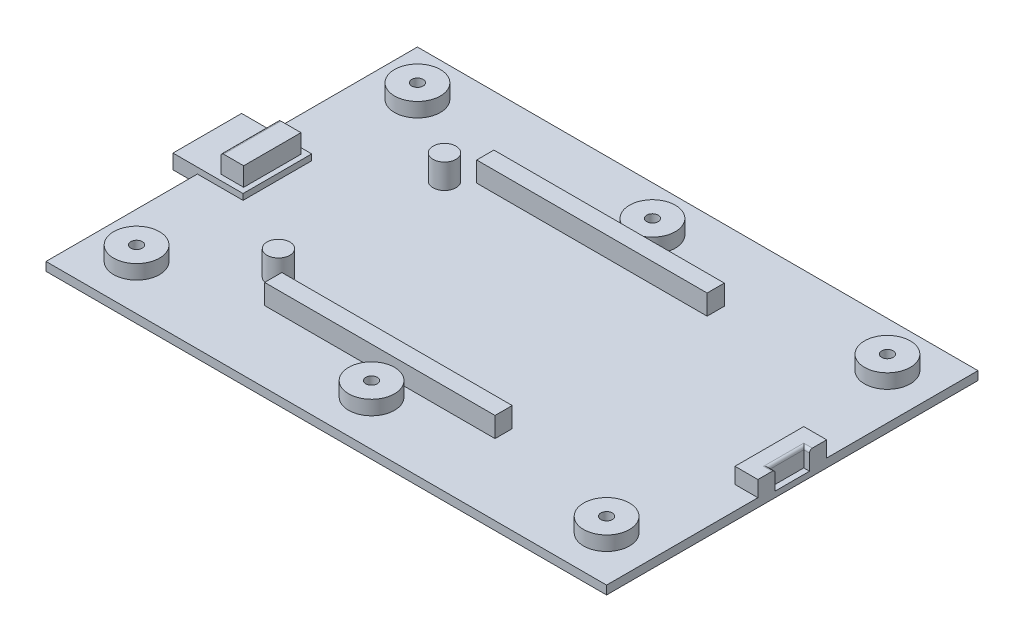
SolidWorks part; units mm, degrees
material "PLA"
ref_plane "前视基准面" through (0, 0, 0) normal (0, 0, 1) x (1, 0, 0)
ref_plane "上视基准面" through (0, 0, 0) normal (0, 1, 0) x (1, 0, 0)
ref_plane "右视基准面" through (0, 0, 0) normal (1, 0, 0) x (0, 0, -1)
other "Configuration Table"
sketch "草图1" plane through (0, 0, 0) normal (0, 1, 0) x (1, 0, 0)
  line L0 (-51.7144, -9.4544) -> (-55.9767, -9.4544)
  line L1 (-51.7144, 16.9583) -> (46.0856, 16.9583)
  line L2 (-51.7144, 16.9583) -> (-51.7144, -9.4544)
  line L3 (-51.7144, -47.8417) -> (46.0856, -47.8417)
  line L4 (46.0856, 16.9583) -> (46.0856, -47.8417)
  line L5 (-51.7144, 16.9583) -> (46.0856, -47.8417) construction
  line L6 (-51.7144, -47.8417) -> (46.0856, 16.9583) construction
  line L7 (-55.9767, -9.4544) -> (-55.9767, -21.429)
  line L8 (-51.8144, -9.3544) -> (-51.8144, 17.0583) construction
  line L9 (46.1856, -47.9417) -> (-51.8144, -47.9417) construction
  line L10 (-55.9767, -21.429) -> (-51.7144, -21.429)
  line L11 (-51.7144, -21.429) -> (-51.7144, -47.8417)
  line L12 (-51.8144, -9.3544) -> (-56.0767, -9.3544) construction
  line L13 (-56.0767, -21.529) -> (-51.8144, -21.529) construction
  line L14 (-56.0767, -9.3544) -> (-56.0767, -21.529) construction
  point P0 (0, 0)
  dimension "D1" = 97.8
  dimension "D2" = 64.8
  dimension "D3" = 0.1
  dimension "D4" = 0.1
  dimension "D5" = 0.1
  dimension "D6" = 0.1
  dimension "D7" = 0.1
extrude "凸台-拉伸1" add sketch "草图1" along normal blind 1.5
sketch "草图2" plane through (0, 0, 0) normal (0, -1, 0) x (1, 0, 0)
  line L0 (-51.7144, 47.8417) -> (46.0856, 47.8417) construction
  line L1 (-2.8144, -16.9583) -> (-2.8144, 10.2547) construction
  line L2 (-51.7144, 21.429) -> (-51.7144, 47.8417) construction
  line L3 (46.0856, -16.9583) -> (-51.7144, -16.9583) construction
  circle A1 centre (-43.8144, 39.9417) radius 5
  circle A4 centre (38.1856, -9.0583) radius 4 construction
  circle A5 centre (38.1856, 39.9417) radius 5
  circle A6 centre (38.1856, -9.0583) radius 5
  circle A7 centre (-43.8144, -9.0583) radius 5
  dimension "D1" = 10
  dimension "D2" = 10
  dimension "D3" = 10
  dimension "D5" = 7.9
  dimension "D6" = 7.9
extrude "防滑切除-拉伸1" cut sketch "草图2" against normal blind 0.5
sketch "草图11" plane through (0, 0, 0) normal (0, -1, 0) x (1, 0, 0)
  line L0 (-55.9767, 9.4544) -> (-55.9767, 21.429) construction
  line L1 (-43.7467, 9.4544) -> (-55.9767, 9.4544)
  line L2 (-43.7467, 9.4544) -> (-43.7467, 21.429)
  line L3 (-43.7467, 21.429) -> (-55.9767, 21.429)
  line L4 (-55.9767, 9.4544) -> (-55.9767, 21.429)
  line L6 (-55.9767, 21.429) -> (-51.7144, 21.429) construction
  line L8 (-51.7144, 9.4544) -> (-55.9767, 9.4544) construction
  line L9 (-48.7467, 14.1953) -> (-48.7467, 16.6882) construction
  line L10 (-26.0744, 32.929) -> (-26.0744, -2.0456) construction
  line L11 (-48.549, 32.929) -> (-26.0744, 32.929) construction
  line L13 (-26.0744, 15.4417) -> (-37.5911, 15.4417) construction
  circle A0 centre (-29.0744, 29.929) radius 2
  circle A1 centre (-29.0744, 0.9544) radius 2
  dimension "D2" = 4
  dimension "D4" = 3
  dimension "D1" = 5
  dimension "D3" = 3
extrude "充电板档板凸台-拉伸5" add sketch "草图11" against normal up to surface (2.54 mm away)
sketch "草图13" plane through (0, 0, 0) normal (0, -1, 0) x (1, 0, 0)
  line L1 (-48.549, 32.929) -> (-26.0744, 32.929) construction
  line L2 (-26.0744, 32.929) -> (-26.0744, -2.0456) construction
  line L3 (-26.0744, 15.4417) -> (-36.6222, 15.4417) construction
  line L4 (-48.7267, 14.1953) -> (-48.7267, 16.6882) construction
  line L5 (-48.6267, 10.4417) -> (-44.6267, 10.4417)
  line L6 (-48.6267, 10.4417) -> (-48.6267, 20.4417)
  line L7 (-48.6267, 20.4417) -> (-44.6267, 20.4417)
  line L8 (-44.6267, 10.4417) -> (-44.6267, 20.4417)
  circle A1 centre (-29.0744, 29.929) radius 2
  circle A2 centre (-29.0744, 0.9544) radius 2
  dimension "D1" = 4
  dimension "D2" = 3
  dimension "D3" = 3
  dimension "D4" = 4
  dimension "D5" = 10
  dimension "D6" = 0.1
extrude "TypeC支撑凸台-拉伸2" add sketch "草图13" against normal up to surface (5.8 mm away)
sketch "草图14" plane through (0, 0, 0) normal (0, -1, 0) x (1, 0, 0)
  line L1 (45.0856, 12.4417) -> (45.0856, 18.4417)
  line L2 (45.0856, 18.4417) -> (46.0856, 18.4417)
  line L3 (46.0856, 18.4417) -> (46.0856, 21.4417)
  line L4 (46.0856, 47.8417) -> (46.0856, -16.9583) construction
  line L5 (46.0856, 21.4417) -> (42.0856, 21.4417)
  line L6 (42.0856, 21.4417) -> (42.0856, 9.4417)
  line L7 (42.0856, 9.4417) -> (46.0856, 9.4417)
  line L8 (46.0856, 9.4417) -> (46.0856, 12.4417)
  line L9 (46.0856, 12.4417) -> (45.0856, 12.4417)
  line L10 (46.0856, 15.4417) -> (41.9652, 15.4417) construction
  line L11 (46.1856, 18.3417) -> (45.1856, 18.3417) construction
  line L12 (45.1856, 18.3417) -> (45.1856, 12.9417) construction
  dimension "D1" = 0.1
  dimension "D2" = 0.1
  dimension "D3" = 3
  dimension "D4" = 3
  dimension "D5" = 3
extrude "LED限位凸台-拉伸3" add sketch "草图14" along normal up to surface (2.75 mm away) from surface
fillet "LED限位圆角1" radius 0.5 4 edges at (-48.6267, 5.8, 15.4417) (45.0856, 4.25, 15.4417) (45.5856, 4.25, 18.4417) (45.5856, 4.25, 12.4417)
sketch "草图15" plane through (0, 0, 0) normal (0, -1, 0) x (1, 0, 0)
  circle A0 centre (-43.8144, -9.0583) radius 2
  circle A1 centre (-43.8144, 39.9417) radius 2
  circle A2 centre (38.1856, -9.0583) radius 2
  circle A3 centre (38.1856, 39.9417) radius 2
  circle A4 centre (38.1856, -9.0583) radius 5 construction
  circle A5 centre (38.1856, 39.9417) radius 5 construction
  circle A6 centre (-2.8144, 39.9417) radius 2
  circle A7 centre (-43.8144, 39.9417) radius 5 construction
  circle A8 centre (-43.8144, -9.0583) radius 4 construction
  circle A9 centre (-2.8144, -9.0583) radius 2
  dimension "D1" = 4
  dimension "D2" = 4
  dimension "D3" = 4
  dimension "D4" = 4
  dimension "D5" = 4
  dimension "D6" = 4
extrude "螺丝孔位切除-拉伸2" cut sketch "草图15" against normal up to next
sketch "草图16" plane through (0, 0, 0) normal (0, -1, 0) x (1, 0, 0)
  circle A0 centre (38.1856, -9.0583) radius 1
  circle A1 centre (38.1856, 39.9417) radius 1
  circle A2 centre (-43.8144, -9.0583) radius 1
  circle A3 centre (-2.8144, 39.9417) radius 1
  circle A8 centre (-43.8144, 39.9417) radius 5 construction
  circle A9 centre (38.1856, -9.0583) radius 5 construction
  circle A10 centre (38.1856, 39.9417) radius 5 construction
  circle A11 centre (-43.8144, -9.0583) radius 5 construction
  circle A12 centre (38.1856, -9.0583) radius 4
  circle A13 centre (38.1856, 39.9417) radius 4
  circle A14 centre (-43.8144, -9.0583) radius 4
  circle A15 centre (-43.8144, 39.9417) radius 4
  circle A16 centre (-43.8144, 39.9417) radius 1
  circle A17 centre (-2.8144, 39.9417) radius 4
  circle A18 centre (-2.8144, -9.0583) radius 4
  circle A19 centre (-2.8144, -9.0583) radius 1
  dimension "D3" = 8
  dimension "D4" = 8
  dimension "D5" = 8
  dimension "D6" = 8
  dimension "D7" = 8
  dimension "D8" = 2
  dimension "D9" = 2
  dimension "D10" = 8
  dimension "D1" = 3
  dimension "D2" = 3
extrude "螺丝孔凸台-拉伸4" add sketch "草图16" along normal up to surface (2.5 mm away) from surface
sketch "草图17" plane through (0, 0, 0) normal (0, -1, 0) x (1, 0, 0)
  line L0 (45.0856, 12.4417) -> (46.1856, 12.4417) construction
  line L1 (45.0856, 18.4417) -> (45.0856, 12.4417) construction
  line L2 (46.1856, 18.4417) -> (45.0856, 18.4417) construction
  line L3 (45.0856, 12.4417) -> (46.0856, 12.4417)
  line L4 (45.0856, 18.4417) -> (45.0856, 12.4417)
  line L5 (46.0856, 18.4417) -> (45.0856, 18.4417)
  line L6 (46.0856, 12.4417) -> (46.0856, 18.4417)
  line L7 (46.0856, 47.8417) -> (46.0856, -16.9583) construction
extrude "LED灯嵌入切除-拉伸2" cut sketch "草图17" along normal blind 0.5 from surface at -1.5 starting at face at (-2.8144, 1.5, -5.0583)
sketch "草图18" plane through (0, 1.5, 0) normal (0, 1, 0) x (1, 0, 0)
  line L0 (-25.9744, 0.5583) -> (-25.9744, -1.4417) construction
  line L1 (14.2256, 4.5583) -> (-25.9744, 4.5583)
  line L2 (14.2256, 4.5583) -> (14.2256, 1.5583)
  line L4 (-25.9744, 4.5583) -> (-25.9744, 1.5583)
  line L7 (14.2256, -32.4417) -> (-25.9744, -32.4417)
  line L8 (14.2256, -32.4417) -> (14.2256, -35.4417)
  line L9 (14.2256, -35.4417) -> (-25.9744, -35.4417)
  line L10 (-25.9744, -32.4417) -> (-25.9744, -35.4417)
  line L11 (14.2256, -31.4417) -> (14.2256, -29.4417) construction
  line L15 (14.2256, 1.5583) -> (-25.9744, 1.5583)
  dimension "D1" = 3
  dimension "D2" = 3
extrude "散热板支撑凸台-拉伸2" add sketch "草图18" along normal up to surface (3.5 mm away)
